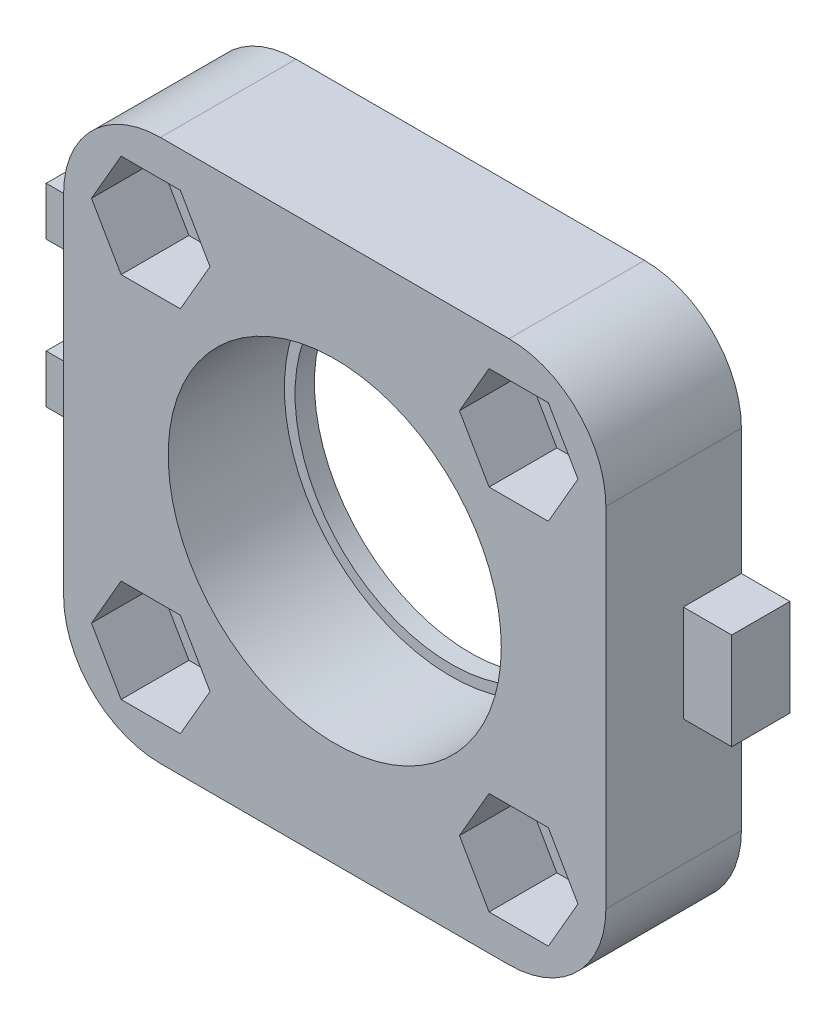
SolidWorks part; units mm, degrees
ref_plane "Alzado" through (0, 0, 0) normal (0, 0, 1) x (1, 0, 0)
ref_plane "Planta" through (0, 0, 0) normal (0, 1, 0) x (1, 0, 0)
ref_plane "Vista lateral" through (0, 0, 0) normal (1, 0, 0) x (0, 0, -1)
sketch "Croquis1" plane through (0, 0, 0) normal (0, 0, 1) x (1, 0, 0)
  line L1 (-14, -14) -> (14, -14)
  line L2 (-14, -14) -> (-14, 14)
  line L3 (-14, 14) -> (14, 14)
  line L4 (14, -14) -> (14, 14)
  line L5 (-14, -14) -> (14, 14) construction
  line L6 (-14, 14) -> (14, -14) construction
  circle A0 centre (0, 0) radius 8.05
  dimension "D1" = 16.1
  dimension "D2" = 28
  dimension "D3" = 28
extrude "Saliente-Extruir1" add sketch "Croquis1" along normal mid plane 1
sketch "Croquis2" plane through (0, 0, 0.5) normal (0, 0, 1) x (1, 0, 0)
  line L4 (14, -14) -> (14, 14)
  line L5 (14, 14) -> (-14, 14)
  line L6 (-14, 14) -> (-14, -14)
  line L7 (-14, -14) -> (14, -14)
  line L8 (14, -14) -> (14, 14)
  line L9 (14, 14) -> (-14, 14)
  line L10 (-14, 14) -> (-14, -14)
  line L11 (-14, -14) -> (14, -14)
  circle A0 centre (0, 0) radius 8.6
  dimension "D2" = 17.2
  dimension "D1" = 0
extrude "Saliente-Extruir2" add sketch "Croquis2" along normal blind 6
sketch "Croquis3" plane through (0, 0, 6.5) normal (0, 0, 1) x (1, 0, 0)
  line L0 (-9.5, 9.5) -> (9.5, 9.5) construction
  line L1 (9.5, 9.5) -> (9.5, -9.5) construction
  line L2 (9.5, -9.5) -> (-9.5, -9.5) construction
  line L3 (-9.5, -9.5) -> (-9.5, 9.5) construction
  line L5 (0, 13.0603) -> (0, -13.8489) construction
  line L6 (15.5492, 0) -> (-17.9148, 0) construction
  line L7 (11.03, 12.15) -> (7.97, 12.15)
  line L8 (-6.44, 9.5) -> (-7.97, 12.15)
  line L9 (-7.97, 12.15) -> (-11.03, 12.15)
  line L10 (-11.03, 12.15) -> (-12.56, 9.5)
  line L11 (-12.56, 9.5) -> (-11.03, 6.85)
  line L12 (-11.03, 6.85) -> (-7.97, 6.85)
  line L13 (-7.97, 6.85) -> (-6.44, 9.5)
  line L14 (7.97, 12.15) -> (6.44, 9.5)
  line L15 (6.44, 9.5) -> (7.97, 6.85)
  line L16 (7.97, 6.85) -> (11.03, 6.85)
  line L17 (11.03, 6.85) -> (12.56, 9.5)
  line L18 (12.56, 9.5) -> (11.03, 12.15)
  line L19 (-7.97, -6.85) -> (-11.03, -6.85)
  line L20 (-11.03, -6.85) -> (-12.56, -9.5)
  line L21 (-12.56, -9.5) -> (-11.03, -12.15)
  line L22 (-11.03, -12.15) -> (-7.97, -12.15)
  line L23 (-7.97, -12.15) -> (-6.44, -9.5)
  line L24 (-6.44, -9.5) -> (-7.97, -6.85)
  line L25 (11.03, -6.85) -> (7.97, -6.85)
  line L26 (7.97, -6.85) -> (6.44, -9.5)
  line L27 (6.44, -9.5) -> (7.97, -12.15)
  line L28 (7.97, -12.15) -> (11.03, -12.15)
  line L29 (11.03, -12.15) -> (12.56, -9.5)
  line L30 (12.56, -9.5) -> (11.03, -6.85)
  circle A0 centre (-9.5, 9.5) radius 1.5 construction
  circle A1 centre (-9.5, -9.5) radius 1.5 construction
  circle A2 centre (9.5, -9.5) radius 1.5 construction
  circle A3 centre (9.5, 9.5) radius 1.5 construction
  circle A4 centre (-9.5, 9.5) radius 2.65 construction
  circle A5 centre (9.5, 9.5) radius 2.65 construction
  circle A6 centre (-9.5, -9.5) radius 2.65 construction
  circle A7 centre (9.5, -9.5) radius 2.65 construction
  point P13 (0, -9.5)
  point P14 (-9.5, 0)
  dimension "D1" = 3
  dimension "D2" = 19
  dimension "D3" = 19
  dimension "D4" = 5.3
extrude "Cortar-Extruir1" cut sketch "Croquis3" against normal blind 3.5
sketch "Croquis6" plane through (0, 0, -0.5) normal (0, 0, -1) x (-1, 0, 0)
  line L0 (-9.5, 9.5) -> (9.5, 9.5) construction
  line L1 (9.5, 9.5) -> (9.5, -9.5) construction
  line L2 (9.5, -9.5) -> (-9.5, -9.5) construction
  line L3 (-9.5, -9.5) -> (-9.5, 9.5) construction
  line L4 (0, 17.9373) -> (0, -16.6332) construction
  line L5 (16.9599, 0) -> (-18.6245, 0) construction
  circle A0 centre (-9.5, 9.5) radius 1.5
  circle A1 centre (9.5, 9.5) radius 1.5
  circle A2 centre (9.5, -9.5) radius 1.5
  circle A3 centre (-9.5, -9.5) radius 1.5
  point P13 (0, 9.5)
  point P14 (-9.5, 0)
  dimension "D1" = 3
  dimension "D2" = 19
  dimension "D3" = 19
extrude "Cortar-Extruir2" cut sketch "Croquis6" against normal blind 23.5
sketch "Croquis7" plane through (0, 0, -0.5) normal (0, 0, -1) x (-1, 0, 0)
  line L0 (14, -14) -> (-14, -14) construction
  line L1 (-5, -14) -> (5, -14)
  line L2 (-5, -14) -> (-5, -18)
  line L3 (-5, -18) -> (5, -18)
  line L4 (5, -14) -> (5, -18)
  line L5 (-14, -14) -> (-14, 14) construction
  line L6 (-14, 2.5) -> (-16.5, 2.5)
  line L7 (-14, 2.5) -> (-14, -2.5)
  line L8 (-14, -2.5) -> (-16.5, -2.5)
  line L9 (-16.5, 2.5) -> (-16.5, -2.5)
  line L10 (14, 14) -> (14, -14) construction
  line L11 (14, 2.5) -> (16.5, 2.5)
  line L12 (14, 2.5) -> (14, -2.5)
  line L13 (14, -2.5) -> (16.5, -2.5)
  line L14 (16.5, 2.5) -> (16.5, -2.5)
  line L15 (0, 20.1506) -> (0, -30.1017) construction
  line L16 (-29.8997, 0) -> (35.1473, 0) construction
  line L17 (14, -5) -> (18.9, -5)
  line L18 (14, 2.5) -> (18.9, 2.5)
  line L19 (14, 2.5) -> (14, 5)
  line L20 (14, 5) -> (18.9, 5)
  line L21 (18.9, 2.5) -> (18.9, 5)
  line L22 (18.9, -2.5) -> (18.9, -5)
  line L23 (14, -2.5) -> (18.9, -2.5)
  line L24 (14, -2.5) -> (14, -5)
  point P23 (-16.5, 0)
  point P24 (16.5, 0)
  point P25 (0, -18)
  line M19 (-14, 14) -> (-14, -14)
  line M20 (-14, -14) -> (14, -14)
  line M21 (14, -14) -> (14, 14)
  dimension "D1" = 10
  dimension "D2" = 4
  dimension "D3" = 2.5
  dimension "D4" = 5
  dimension "D5" = 5
  dimension "D6" = 2.5
  dimension "D7" = 2.5
  dimension "D8" = 4.9
  dimension "D9" = 18
extrude "Saliente-Extruir3" add sketch "Croquis7" against normal blind 3 contours L6 L9 L8 M19 | L4 L2 L3 M20 | L23 L13 L17 L22 M21 | L14 L11 L13 M21 | L18 L21 L20 L11 M21
fillet "Redondeo1" radius 5 4 edges at (-14, -14, 3) (14, -14, 3) (14, 14, 3) (-14, 14, 3)
